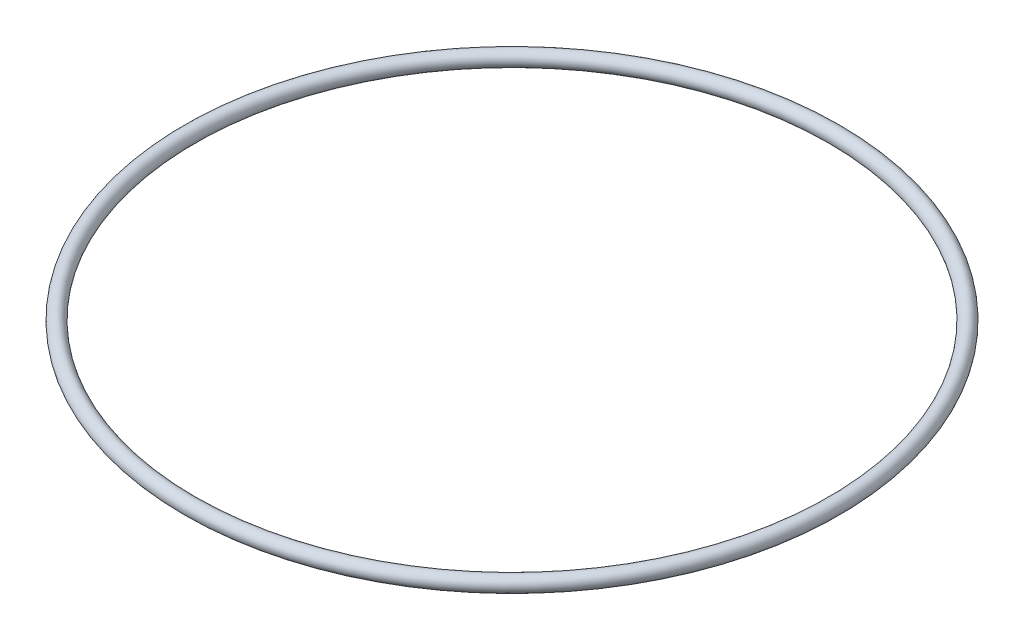
SolidWorks part; units mm, degrees
ref_plane "Front Plane" through (0, 0, 0) normal (0, 0, 1) x (1, 0, 0)
ref_plane "Top Plane" through (0, 0, 0) normal (0, 1, 0) x (1, 0, 0)
ref_plane "Right Plane" through (0, 0, 0) normal (1, 0, 0) x (0, 0, -1)
sketch "Sketch1" plane through (0, 0, 0) normal (1, 0, 0) x (0, 0, -1)
  line L0 (0, 0) -> (0, 2) construction
  circle A0 centre (45.375, 0) radius 1.05
  point P5 (0, 0)
  dimension "D1" = 2.1
  dimension "D2" = 45.375
  dimension "D3" = 2
revolve "Revolve1" add sketch "Sketch1" angle 360 about L0
